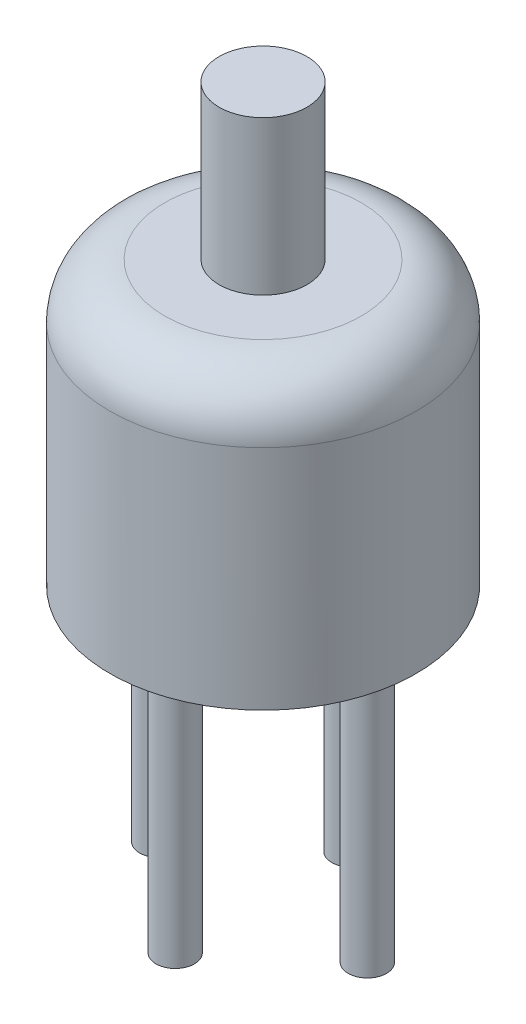
SolidWorks part; units mm, degrees
ref_plane "Front Plane" through (0, 0, 0) normal (0, 0, 1) x (1, 0, 0)
ref_plane "Top Plane" through (0, 0, 0) normal (0, 1, 0) x (1, 0, 0)
ref_plane "Right Plane" through (0, 0, 0) normal (1, 0, 0) x (0, 0, -1)
sketch "Sketch1" plane through (0, 0, 0) normal (0, 1, 0) x (1, 0, 0)
  circle A0 centre (0, 0) radius 13.95
  dimension "D1" = 27.9
extrude "Boss-Extrude1" add sketch "Sketch1" along normal blind 25.7
fillet "Fillet1" radius 5 1 edges at (0, 25.7, 13.95)
sketch "Sketch2" plane through (0, 25.7, 0) normal (0, 1, 0) x (1, 0, 0)
  circle A0 centre (0, 0) radius 4
  dimension "D1" = 8
extrude "Boss-Extrude2" add sketch "Sketch2" along normal blind 14
sketch "Sketch3" plane through (0, 0, 0) normal (0, -1, 0) x (1, 0, 0)
  line L0 (13.95, 0) -> (-13.95, 0)
  line L1 (0, 13.95) -> (0, -13.95)
  circle A0 centre (0, 0) radius 13.95 construction
  circle A1 centre (0, 8) radius 1.75
  circle A2 centre (9.5, 0) radius 1.75
  circle A3 centre (0, -8) radius 1.75
  circle A4 centre (-9.5, 0) radius 1.75
  dimension "D1" = 3.5
  dimension "D2" = 3.5
  dimension "D3" = 3.5
  dimension "D4" = 3.5
  dimension "D5" = 8
  dimension "D6" = 8
  dimension "D7" = 9.5
  dimension "D8" = 9.5
extrude "Boss-Extrude3" add sketch "Sketch3" along normal blind 25 contours L1 A1 | L1 A1 | L0 A4 | L0 A4 | L1 A3 | L0 A2 | L0 A2
